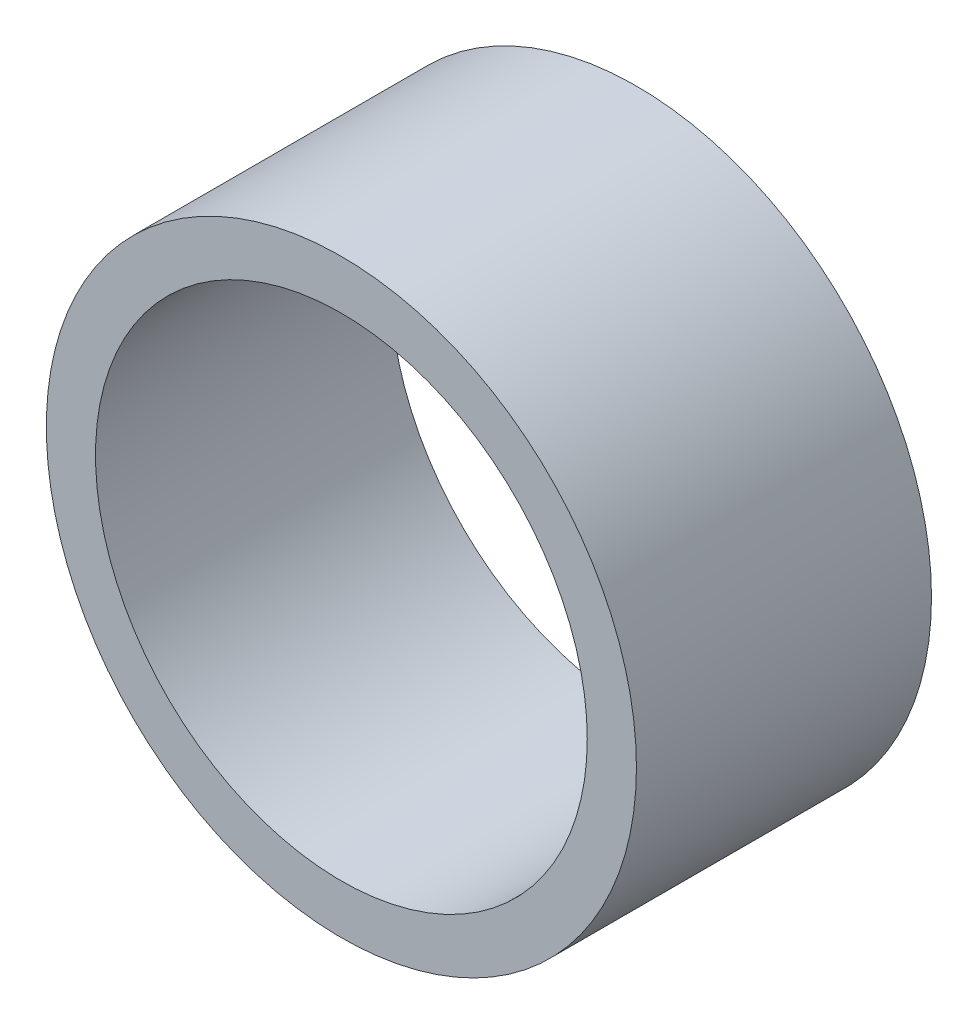
SolidWorks part; units mm, degrees
ref_plane "前视基准面" through (0, 0, 0) normal (0, 0, 1) x (1, 0, 0)
ref_plane "上视基准面" through (0, 0, 0) normal (0, 1, 0) x (1, 0, 0)
ref_plane "右视基准面" through (0, 0, 0) normal (1, 0, 0) x (0, 0, -1)
sketch "草图1" plane through (0, 0, 0) normal (0, 0, 1) x (1, 0, 0)
  circle A0 centre (0, 0) radius 6
  circle A1 centre (0, 0) radius 5
  dimension "D1" = 10
  dimension "D2" = 12
extrude "凸台-拉伸1" add sketch "草图1" along normal blind 6
